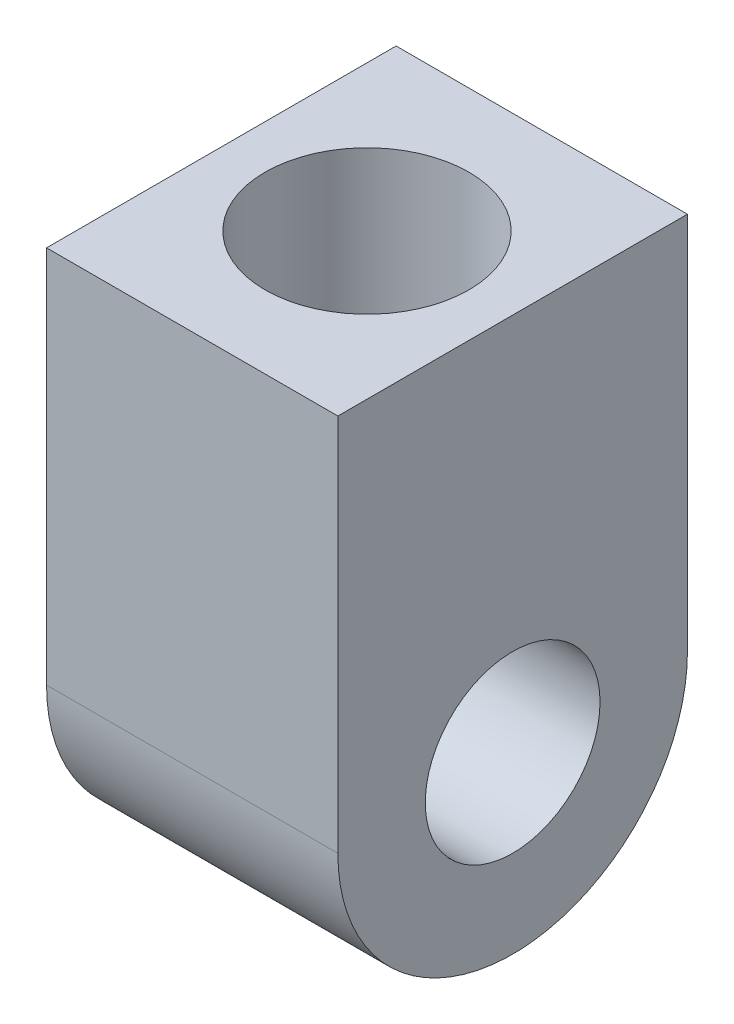
SolidWorks part; units mm, degrees
ref_plane "前视基准面" through (0, 0, 0) normal (0, 0, 1) x (1, 0, 0)
ref_plane "上视基准面" through (0, 0, 0) normal (0, 1, 0) x (1, 0, 0)
ref_plane "右视基准面" through (0, 0, 0) normal (1, 0, 0) x (0, 0, -1)
sketch "草图1" plane through (0, 0, 0) normal (1, 0, 0) x (0, 0, -1)
  circle A0 centre (0, 0) radius 3
  circle A1 centre (0, 0) radius 6
  dimension "D1" = 12
  dimension "D2" = 6
extrude "凸台-拉伸1" add sketch "草图1" along normal blind 10
sketch "草图2" plane through (0, 0, 0) normal (0, 1, 0) x (1, 0, 0)
  line L0 (10, 6) -> (0, -6) construction
  line L1 (10, 6) -> (0, 6) construction
  line L2 (10, -6) -> (0, -6)
  line L3 (10, -6) -> (10, 6)
  line L4 (10, 6) -> (0, 6)
  line L5 (0, -6) -> (0, 6)
  line L6 (10, -6) -> (0, 6) construction
  line L7 (10, 6) -> (0, -6) construction
  line L8 (0, 6) -> (0, -6) construction
  circle A0 centre (5, 0) radius 3.5
extrude "凸台-拉伸2" add sketch "草图2" along normal blind 13
sketch "草图4" plane through (10, 0, 0) normal (1, 0, 0) x (0, 0, -1)
  circle A0 centre (0, 0) radius 3
extrude "切除-拉伸1" cut sketch "草图4" against normal blind 13
sketch "草图5" plane through (0, 13, 0) normal (0, 1, 0) x (1, 0, 0)
  circle A0 centre (5, 0) radius 3.5
extrude "切除-拉伸2" cut sketch "草图5" against normal blind 8.5
